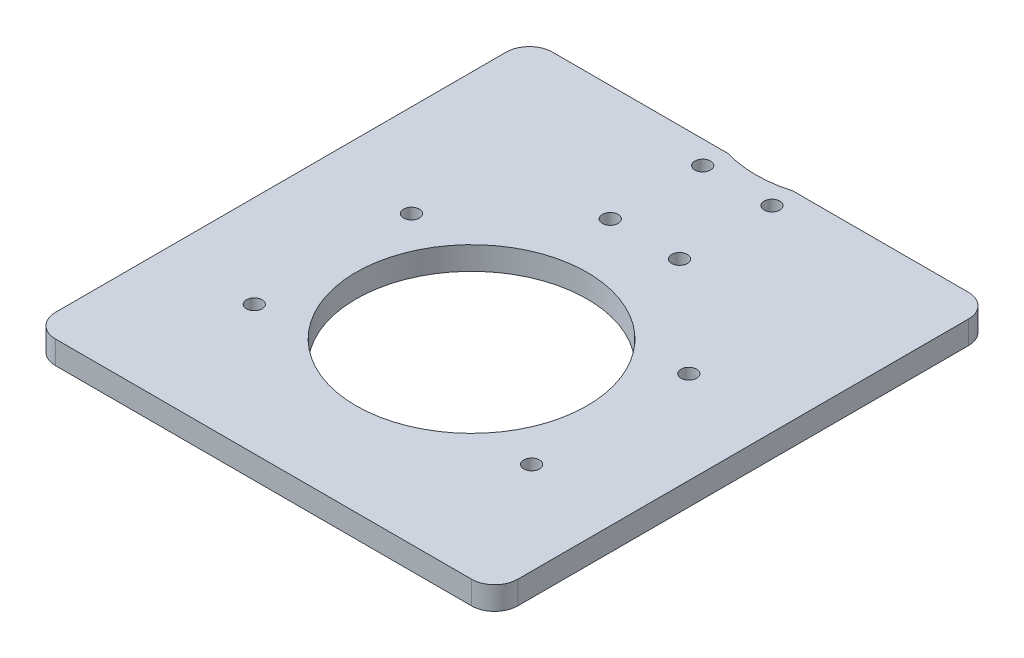
SolidWorks part; units mm, degrees
material "AISI 304"
ref_plane "前视基准面" through (0, 0, 0) normal (0, 0, 1) x (1, 0, 0)
ref_plane "上视基准面" through (0, 0, 0) normal (0, 1, 0) x (1, 0, 0)
ref_plane "右视基准面" through (0, 0, 0) normal (1, 0, 0) x (0, 0, -1)
sketch "Sketch1" plane through (0, 0, 0) normal (0, 1, 0) x (1, 0, 0)
  line L1 (100, -107.5) -> (-100, -107.5)
  line L2 (100, -107.5) -> (100, 107.5)
  line L3 (100, 107.5) -> (-100, 107.5)
  line L4 (-100, -107.5) -> (-100, 107.5)
  line L5 (100, -107.5) -> (-100, 107.5) construction
  line L6 (100, 107.5) -> (-100, -107.5) construction
  point P0 (0, 0)
  dimension "D1" = 200
  dimension "D2" = 215
extrude "Extrude1" add sketch "Sketch1" along normal blind 10
sketch "Sketch2" plane through (0, 10, 0) normal (0, 1, 0) x (1, 0, 0)
  line L0 (0, 107.5) -> (0, -107.5) construction
  line L1 (60, -51.5) -> (-60, -51.5) construction
  line L2 (60, -51.5) -> (60, 16.5) construction
  line L3 (60, 16.5) -> (-60, 16.5) construction
  line L4 (-60, -51.5) -> (-60, 16.5) construction
  line L5 (60, -51.5) -> (-60, 16.5) construction
  line L6 (60, 16.5) -> (-60, -51.5) construction
  line L7 (100, 107.5) -> (-100, 107.5) construction
  line L8 (-100, -107.5) -> (100, -107.5) construction
  line L10 (15, 57.5) -> (-15, 57.5) construction
  line L11 (15, 57.5) -> (15, 97.5) construction
  line L12 (15, 97.5) -> (-15, 97.5) construction
  line L13 (-15, 57.5) -> (-15, 97.5) construction
  line L14 (15, 57.5) -> (-15, 97.5) construction
  line L15 (15, 97.5) -> (-15, 57.5) construction
  point P0 (0, -17.5)
  point P12 (0, 77.5)
  dimension "D1" = 120
  dimension "D2" = 68
  dimension "D3" = 125
  dimension "D4" = 30
  dimension "D5" = 40
  dimension "D6" = 30
hole_wizard "M8 Tapped Hole1" positions "3DSketch1" profile "Sketch3" tap size "M8" standard "GB"
sketch3d "3DSketch1"
  point P0 (-60, 10, -16.5)
  point P3 (60, 10, -16.5)
  point P6 (-60, 10, 51.5)
  point P9 (60, 10, 51.5)
sketch "Sketch3" plane through (-60, 10, -16.5) normal (1, 0, 0) x (0, 0, 1)
  line L0 (0, 0) -> (0, 21.7929)
  line L1 (0, 21.7929) -> (3.4, 19.75)
  line L2 (3.4, 19.75) -> (3.4, 0)
  line L5 (3.4, 0) -> (0, 0)
  line L10 (0, 21.7929) -> (-3.4, 19.75) construction
  line L11 (0, -6.35) -> (0, 107.95) construction
  dimension "螺纹孔钻头直径" = 6.8
  dimension "螺纹孔钻头深度" = 19.75
  dimension "导头角度" = 118
hole_wizard "M8 Tapped Hole2" positions "3DSketch2" profile "Sketch4" tap size "M8" standard "GB"
sketch3d "3DSketch2"
  point P0 (-15, 10, -97.5)
  point P3 (-15, 10, -57.5)
  point P6 (15, 10, -57.5)
  point P9 (15, 10, -97.5)
sketch "Sketch4" plane through (-15, 10, -97.5) normal (1, 0, 0) x (0, 0, 1)
  line L0 (0, 0) -> (0, 21.7929)
  line L1 (0, 21.7929) -> (3.4, 19.75)
  line L2 (3.4, 19.75) -> (3.4, 0)
  line L5 (3.4, 0) -> (0, 0)
  line L10 (0, 21.7929) -> (-3.4, 19.75) construction
  line L11 (0, -6.35) -> (0, 107.95) construction
  dimension "螺纹孔钻头直径" = 6.8
  dimension "螺纹孔钻头深度" = 19.75
  dimension "导头角度" = 118
sketch "Sketch5" plane through (0, 10, 0) normal (0, 1, 0) x (1, 0, 0)
  line L2 (100, 107.5) -> (-100, 107.5) construction
  circle A0 centre (0, -17.5) radius 50
  point P5 (0, 0)
  dimension "D1" = 100
  dimension "D2" = 125
extrude "Extrude2" cut sketch "Sketch5" against normal blind 10
sketch "Sketch6" plane through (0, 10, 0) normal (0, 1, 0) x (1, 0, 0)
  line L0 (100, 107.5) -> (-100, 107.5) construction
  circle A0 centre (0, 155.5) radius 50
  dimension "D1" = 100
  dimension "D2" = 48
extrude "Extrude3" cut sketch "Sketch6" against normal blind 10
fillet "Fillet1" radius 10 4 edges at (100, 5, 107.5) (-100, 5, 107.5) (-100, 5, -107.5) (100, 5, -107.5)
sketch "Sketch7" plane through (0, 0, 0) normal (0, 1, 0) x (1, 0, 0)
  line L1 (56, -73.5) -> (-56, -73.5) construction
  line L2 (56, -73.5) -> (56, 38.5) construction
  line L3 (56, 38.5) -> (-56, 38.5) construction
  line L4 (-56, -73.5) -> (-56, 38.5) construction
  line L5 (56, -73.5) -> (-56, 38.5) construction
  line L6 (56, 38.5) -> (-56, -73.5) construction
  point P0 (0, -17.5)
  dimension "D1" = 112
hole_wizard "M6 Tapped Hole1" positions "3DSketch3" profile "Sketch9" tap size "M6" standard "GB"
sketch3d "3DSketch3"
  point P0 (-56, 0, -38.5)
  point P3 (56, 0, -38.5)
  point P6 (-56, 0, 73.5)
  point P9 (56, 0, 73.5)
sketch "Sketch9" plane through (-56, 0, -38.5) normal (1, 0, 0) x (0, 0, -1)
  line L0 (0, 0) -> (0, 9.5022)
  line L1 (0, 9.5022) -> (2.5, 8)
  line L2 (2.5, 8) -> (2.5, 0)
  line L5 (2.5, 0) -> (0, 0)
  line L10 (0, 9.5022) -> (-2.5, 8) construction
  line L11 (0, -6.35) -> (0, 107.95) construction
  dimension "螺纹孔钻头直径" = 5
  dimension "螺纹孔钻头深度" = 8
  dimension "导头角度" = 118
